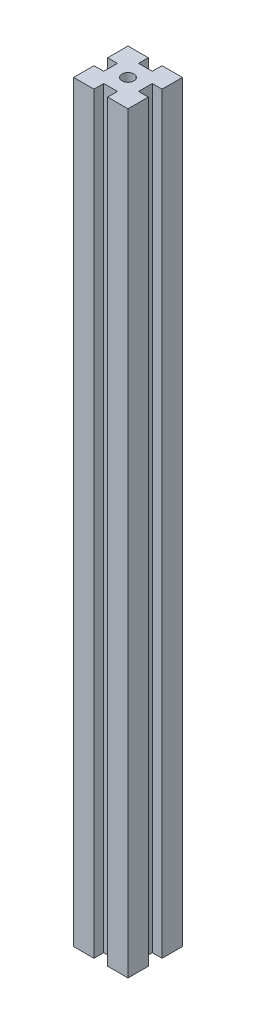
SolidWorks part; units mm, degrees
ref_plane "Front Plane" through (0, 0, 0) normal (0, 0, 1) x (1, 0, 0)
ref_plane "Top Plane" through (0, 0, 0) normal (0, 1, 0) x (1, 0, 0)
ref_plane "Right Plane" through (0, 0, 0) normal (1, 0, 0) x (0, 0, -1)
sketch "Sketch1" plane through (0, 0, 0) normal (0, 1, 0) x (1, 0, 0)
  line L0 (9.35, 25) -> (9.35, 20.5)
  line L1 (0, 0) -> (9.35, 0)
  line L2 (0, 0) -> (0, 9.35)
  line L3 (0, 25) -> (9.35, 25)
  line L4 (25, 0) -> (25, 9.35)
  line L5 (9.35, 20.5) -> (15.65, 20.5)
  line L6 (15.65, 20.5) -> (15.65, 25)
  line L7 (25, 15.65) -> (20.5, 15.65)
  line L8 (20.5, 15.65) -> (20.5, 9.35)
  line L9 (20.5, 9.35) -> (25, 9.35)
  line L10 (15.65, 0) -> (15.65, 4.5)
  line L11 (15.65, 4.5) -> (9.35, 4.5)
  line L12 (9.35, 4.5) -> (9.35, 0)
  line L13 (0, 9.35) -> (4.5, 9.35)
  line L14 (4.5, 9.35) -> (4.5, 15.65)
  line L15 (4.5, 15.65) -> (0, 15.65)
  line L16 (15.65, 25) -> (25, 25)
  line L17 (0, 15.65) -> (0, 25)
  line L18 (25, 15.65) -> (25, 25)
  line L19 (15.65, 0) -> (25, 0)
  circle A0 centre (12.5, 12.5) radius 2.75
  point P12 (4.5, 12.5)
  point P14 (12.5, 20.5)
  point P30 (12.5, 12.5)
  dimension "D2" = 5.5
  dimension "D1" = 25
  dimension "D3" = 6.3
  dimension "D4" = 4.5
  dimension "D6" = 12.5
  dimension "D5" = 4
extrude "Boss-Extrude1" add sketch "Sketch1" along normal blind 346
